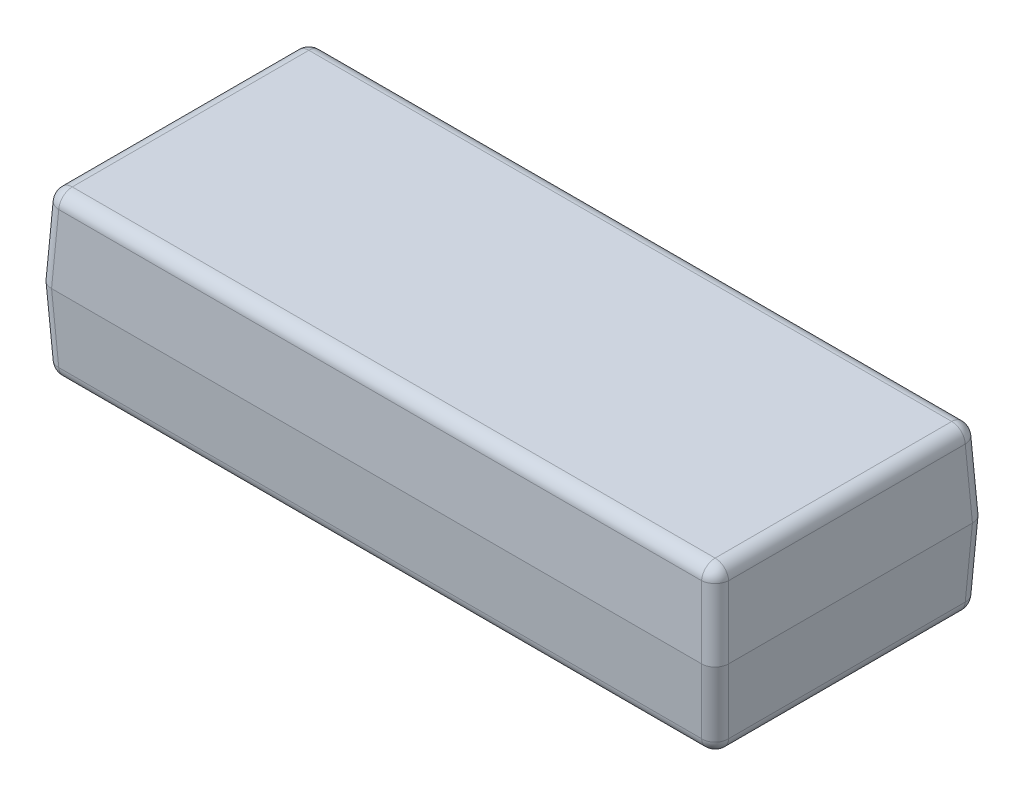
SolidWorks part; units mm, degrees
ref_plane "Front Plane" through (0, 0, 0) normal (0, 0, 1) x (1, 0, 0)
ref_plane "Top Plane" through (0, 0, 0) normal (0, 1, 0) x (1, 0, 0)
ref_plane "Right Plane" through (0, 0, 0) normal (1, 0, 0) x (0, 0, -1)
sketch "Sketch1" plane through (0, 0, 0) normal (0, 1, 0) x (1, 0, 0)
  line L1 (-62.5, 25) -> (62.5, 25)
  line L2 (-62.5, 25) -> (-62.5, -25)
  line L3 (-62.5, -25) -> (62.5, -25)
  line L4 (62.5, 25) -> (62.5, -25)
  line L5 (-62.5, 25) -> (62.5, -25) construction
  line L6 (-62.5, -25) -> (62.5, 25) construction
  point P0 (0, 0)
extrude "Boss-Extrude1" add sketch "Sketch1" along normal blind 15 draft 3
fillet "Fillet1" radius 2.5 8 edges at (62.1069, 7.5, 24.6069) (-62.1069, 7.5, -24.6069) (-62.1069, 7.5, 24.6069) (62.1069, 7.5, -24.6069) (0, 15, -24.2139) (61.7139, 15, 0) (0, 15, 24.2139) (-61.7139, 15, 0)
sketch "Sketch2" plane through (0, 0, 0) normal (0, -1, 0) x (1, 0, 0)
  line L0 (60.0034, -25) -> (-60.0034, -25) construction
  line L1 (-62.5, 25) -> (62.5, 25)
  line L2 (-62.5, 25) -> (-62.5, -25)
  line L3 (-62.5, -25) -> (62.5, -25)
  line L4 (62.5, 25) -> (62.5, -25)
  line L5 (-62.5, 25) -> (62.5, -25) construction
  line L6 (-62.5, -25) -> (62.5, 25) construction
  point P0 (0, 0)
extrude "Boss-Extrude2" add sketch "Sketch2" along normal blind 15 draft 3 separate body
fillet "Fillet2" radius 2.5 8 edges at (-61.7139, -15, 0) (-62.1069, -7.5, 24.6069) (0, -15, 24.2139) (62.1069, -7.5, 24.6069) (61.7139, -15, 0) (0, -15, -24.2139) (62.1069, -7.5, -24.6069) (-62.1069, -7.5, -24.6069)
